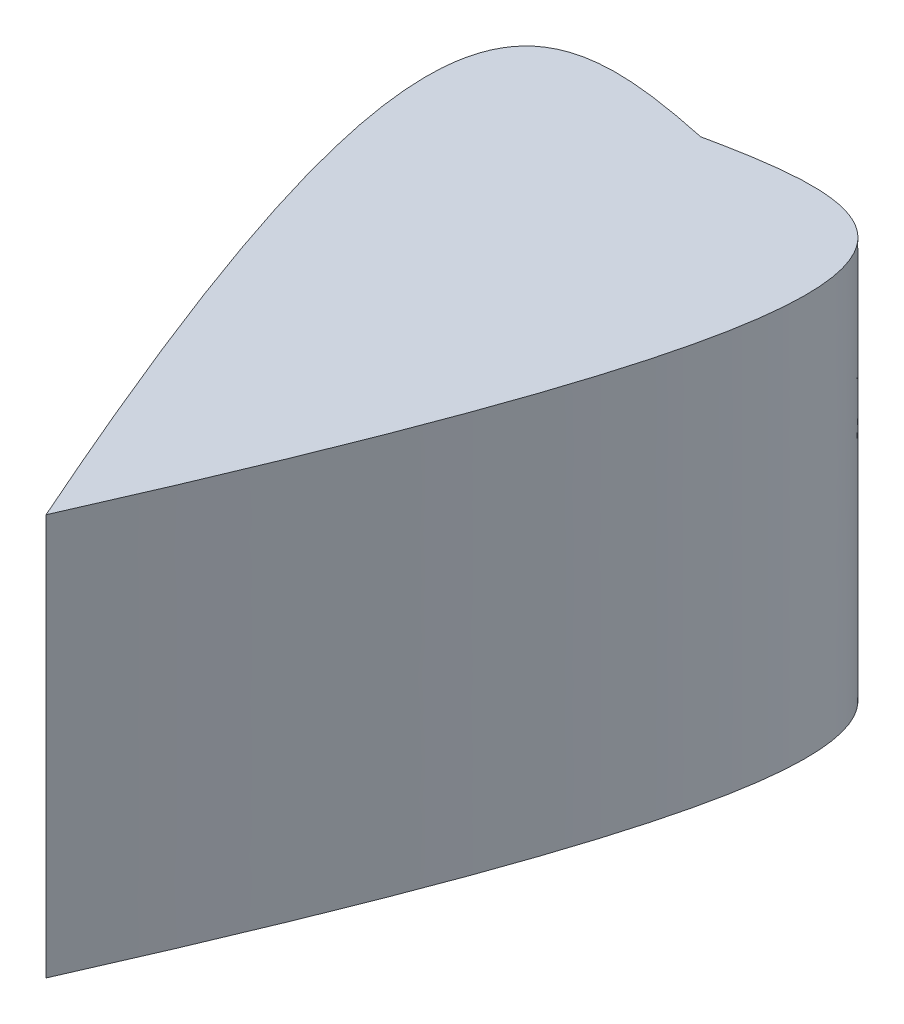
SolidWorks part; units mm, degrees
ref_plane "Front Plane" through (0, 0, 0) normal (0, 0, 1) x (1, 0, 0)
ref_plane "Top Plane" through (0, 0, 0) normal (0, 1, 0) x (1, 0, 0)
ref_plane "Right Plane" through (0, 0, 0) normal (1, 0, 0) x (0, 0, -1)
ref_plane "Plane1" through (0, 607.7691, 0) normal (0, 1, 0) x (1, 0, 0)
sketch "Sketch3" plane through (0, 607.7691, 0) normal (0, 1, 0) x (1, 0, 0)
  line L0 (127.8646, -2251.5351) -> (127.8646, -2628.06) construction
  line L1 (112.8646, -2251.5351) -> (142.8646, -2251.5351) construction
  spline S0 degree 3 poles (127.8646, -1926.6606) (330.0039, -1883.7764) (425.1906, -1907.4101) (127.8646, -2579.3495) knots 0 0 0 0 1 1 1 1
  spline S1 degree 3 poles (127.8646, -1926.6606) (-74.2747, -1883.7764) (-169.4614, -1907.4101) (127.8646, -2579.3495) knots 0 0 0 0 1 1 1 1
  point P4 (127.8646, -1926.6606)
  point P7 (229.3174, -1913.406)
  point P10 (127.8646, -2579.3495)
extrude "Boss-Extrude1" add sketch "Sketch3" along normal blind 400
